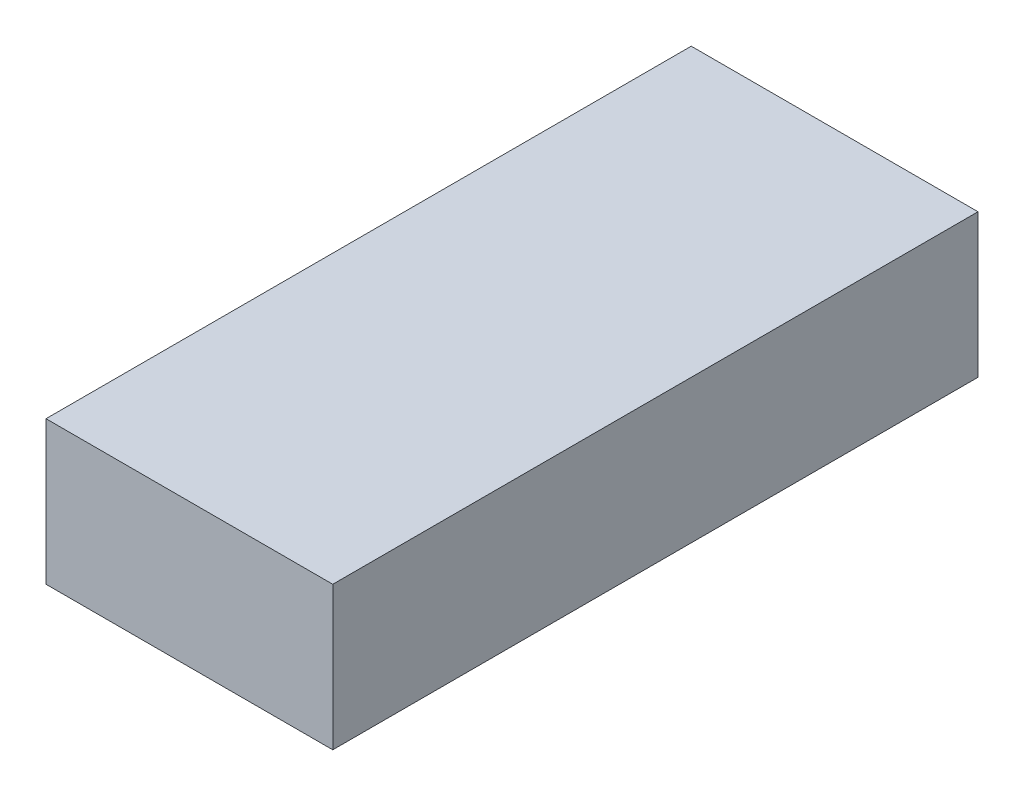
SolidWorks part; units mm, degrees
ref_plane "Front Plane" through (0, 0, 0) normal (0, 0, 1) x (1, 0, 0)
ref_plane "Top Plane" through (0, 0, 0) normal (0, 1, 0) x (1, 0, 0)
ref_plane "Right Plane" through (0, 0, 0) normal (1, 0, 0) x (0, 0, -1)
sketch "Sketch1" plane through (0, 0, 0) normal (0, 1, 0) x (1, 0, 0)
  line L1 (0, 0) -> (20, 0)
  line L2 (0, 0) -> (0, 45)
  line L3 (0, 45) -> (20, 45)
  line L4 (20, 0) -> (20, 45)
  dimension "D1" = 45
  dimension "D2" = 20
extrude "Boss-Extrude1" add sketch "Sketch1" along normal blind 10
